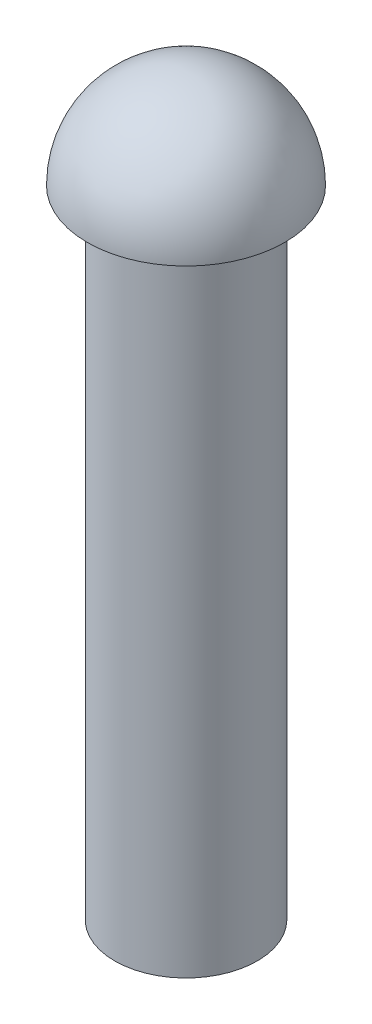
SolidWorks part; units mm, degrees
ref_plane "前视基准面" through (0, 0, 0) normal (0, 0, 1) x (1, 0, 0)
ref_plane "上视基准面" through (0, 0, 0) normal (0, 1, 0) x (1, 0, 0)
ref_plane "右视基准面" through (0, 0, 0) normal (1, 0, 0) x (0, 0, -1)
other "Configuration Table"
sketch "草图1" plane through (0, 0, 0) normal (0, 1, 0) x (1, 0, 0)
  line L0 (0, 9) -> (0, -9)
  arc A0 (0, -9) -> (0, 9) centre (0, 0) ccw
  dimension "D1" = 18
revolve "旋转1" add sketch "草图1" angle 180 about L0
sketch "草图8" plane through (0, 0, 0) normal (1, 0, 0) x (0, 0, -1)
  line L1 (0, 0) -> (8.7, 0)
  line L2 (0, 0) -> (0, 2.3043)
  line L3 (0, 2.3043) -> (8.7, 2.3043)
  line L4 (8.7, 0) -> (8.7, 2.3043)
  arc A0 (9, 0) -> (-9, 0) centre (0, 0) ccw construction
  dimension "D1" = 8.7
  dimension "D2" = 2.3043
sketch "草图6" plane through (0, 0, 0) normal (1, 0, 0) x (0, 0, -1)
  line L1 (0, 0) -> (6.5, 0)
  line L2 (0, 0) -> (0, -58)
  line L3 (0, -58) -> (6.5, -58)
  line L4 (6.5, 0) -> (6.5, -58)
  dimension "D1" = 6.5
  dimension "D2" = 58
revolve "旋转2" add sketch "草图6" angle 360 about L2
